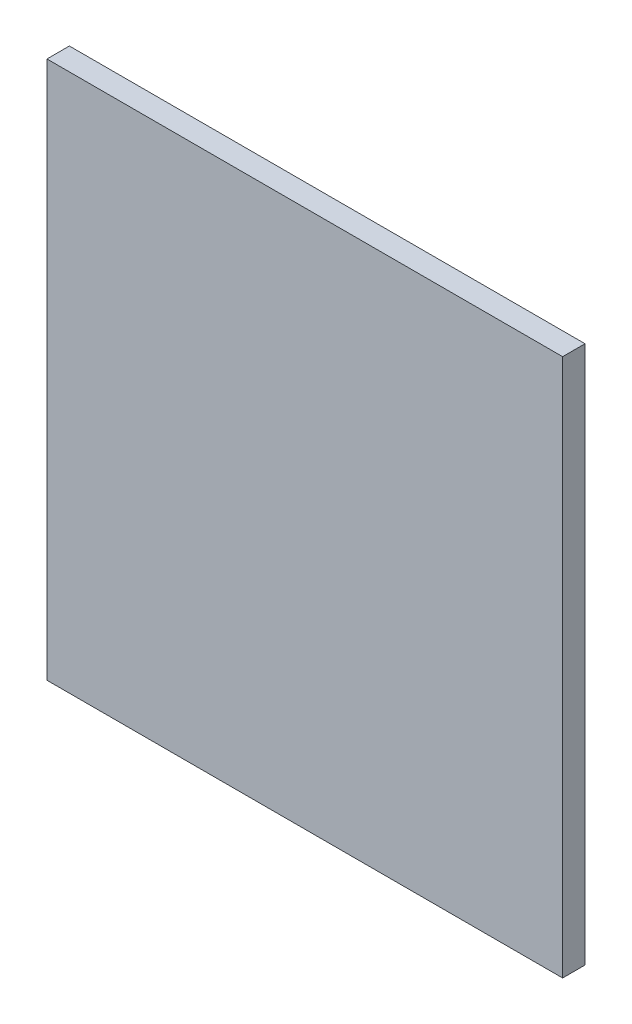
SolidWorks part; units mm, degrees
material "PMMA"
ref_plane "Front Plane" through (0, 0, 0) normal (0, 0, 1) x (1, 0, 0)
ref_plane "Top Plane" through (0, 0, 0) normal (0, 1, 0) x (1, 0, 0)
ref_plane "Right Plane" through (0, 0, 0) normal (1, 0, 0) x (0, 0, -1)
sketch "Sketch1" plane through (0, 0, 0) normal (0, 0, 1) x (1, 0, 0)
  line L1 (-57.5, 120) -> (57.5, 120)
  line L2 (-57.5, 120) -> (-57.5, 0)
  line L3 (-57.5, 0) -> (57.5, 0)
  line L4 (57.5, 120) -> (57.5, 0)
  point P4 (0, 0)
  dimension "D1" = 115
  dimension "D2" = 120
extrude "Boss-Extrude1" add sketch "Sketch1" along normal blind 5
